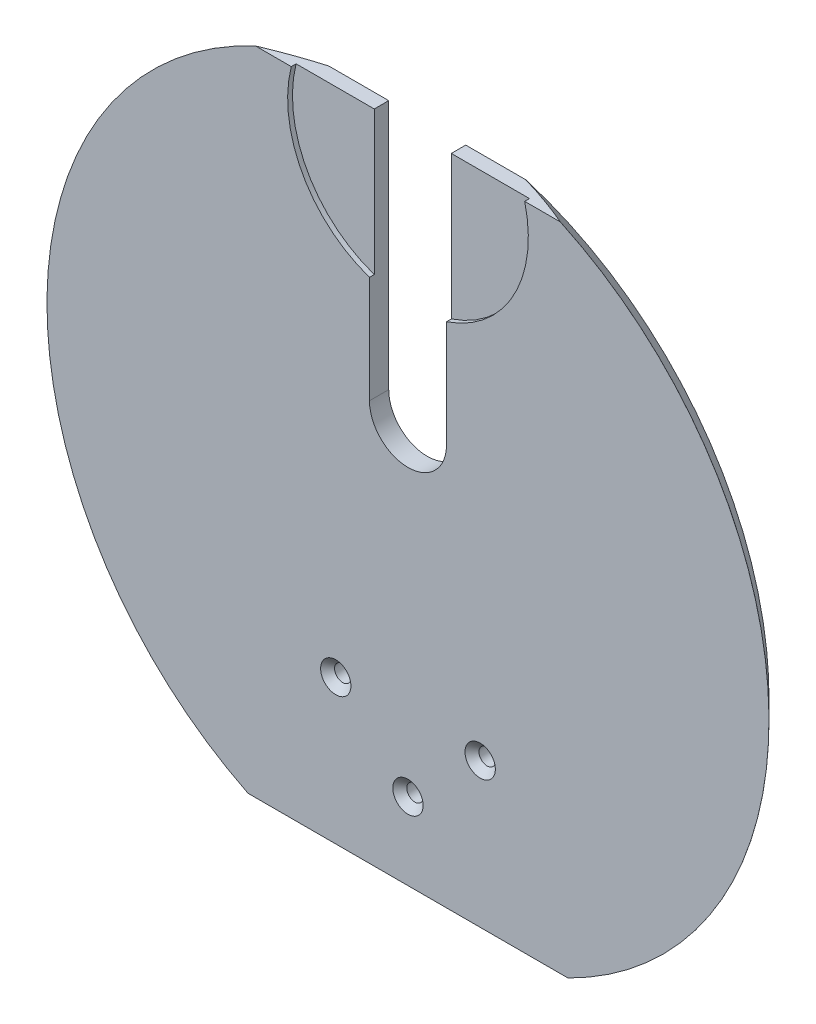
SolidWorks part; units mm, degrees
material "PET"
ref_plane "Front Plane" through (0, 0, 0) normal (0, 0, 1) x (1, 0, 0)
ref_plane "Top Plane" through (0, 0, 0) normal (0, 1, 0) x (1, 0, 0)
ref_plane "Right Plane" through (0, 0, 0) normal (1, 0, 0) x (0, 0, -1)
sketch "Sketch1" plane through (0, 0, 0) normal (0, 0, 1) x (1, 0, 0)
  line L1 (-33.2265, -67.2384) -> (-33.2265, -65) construction
  line L2 (-33.2265, -67.2384) -> (33.2265, -67.2384)
  line L4 (-31.6386, 68) -> (31.6386, 68)
  line L5 (-33.2265, -65) -> (33.2265, -65) construction
  line L6 (82.5, 0) -> (-82.5, 0) construction
  arc A4 (33.2265, -65) -> (26.5518, 68) centre (0, 0) ccw construction
  arc A6 (-31.6386, 68) -> (-33.2265, -67.2384) centre (0, 0) ccw
  arc A7 (-26.5518, 68) -> (-33.2265, -65) centre (0, 0) ccw construction
  arc A8 (33.2265, -67.2384) -> (31.6386, 68) centre (0, 0) ccw
  point P7 (26.6086, 68)
  point P8 (27.887, 67.4634)
  point P9 (0, 0)
  dimension "D2" = 150
  dimension "D3" = 146
  dimension "D9" = 68
  dimension "D11" = 65
extrude "Boss-Extrude2" add sketch "Sketch1" along normal blind 4
sketch "Sketch2" plane through (0, 0, 4) normal (0, 0, 1) x (1, 0, 0)
  line L0 (0, -75.5596) -> (0, 75.5596) construction
  line L2 (-33.2265, -67.2384) -> (33.2265, -67.2384) construction
  point P3 (-15, -37.2384)
  point P6 (0, -51.2384)
  point P9 (0, 0)
  point P10 (0, 0)
  point P13 (15, -37.2384)
  point P18 (5.096, -51.2384)
  dimension "D1" = 30
  dimension "D2" = 14
  dimension "D3" = 16
hole_wizard "CSK for M3 Countersunk Flat Head Screw1" positions "Sketch2" profile "Sketch3" countersink size "M3" standard "ISO" end condition up to next
sketch "Sketch3" plane through (-15, -37.2384, 4) normal (1, 0, 0) x (0, -1, 0)
  line L0 (0, 0) -> (0, 4)
  line L1 (0, 4) -> (1.7, 4)
  line L2 (1.7, 4) -> (1.7, 1.45)
  line L3 (1.7, 1.45) -> (3.15, 0)
  line L5 (3.15, 0) -> (0, 0)
  line L6 (-1.7, 1.45) -> (-3.15, 0) construction
  line L11 (0, -6.35) -> (0, 107.95) construction
  dimension "Thru Hole Dia." = 3.4
  dimension "Thru Hole Depth" = 4
  dimension "Near C'Sink Dia." = 6.3
  dimension "Near C'Sink Angle" = 90
sketch "Sketch4" plane through (0, 0, 4) normal (0, 0, 1) x (1, 0, 0)
  line L0 (0, -2.2) -> (0, 2.2) construction
  line L8 (-8, 16) -> (-8, 68)
  line L9 (-8, 68) -> (8, 68)
  line L10 (8, 16) -> (8, 68)
  line L12 (31.6386, 68) -> (-31.6386, 68) construction
  arc A0 (-8, 16) -> (8, 16) centre (0, 16) ccw
  point P3 (0, 8)
  dimension "D1" = 8
  dimension "D2" = 60
extrude "Cut-Extrude1" cut sketch "Sketch4" against normal up to next
sketch "Sketch5" plane through (0, 0, 4) normal (0, 0, 1) x (1, 0, 0)
  circle A0 centre (0, 61.9) radius 25
  dimension "D1" = 50
  dimension "D2" = 61.9
extrude "Cut-Extrude2" cut sketch "Sketch5" against normal blind 1
chamfer "Chamfer3" distance 3.99 2 edges at (-74.9948, 0.8806, 0) (74.9948, 0.8806, 0)
